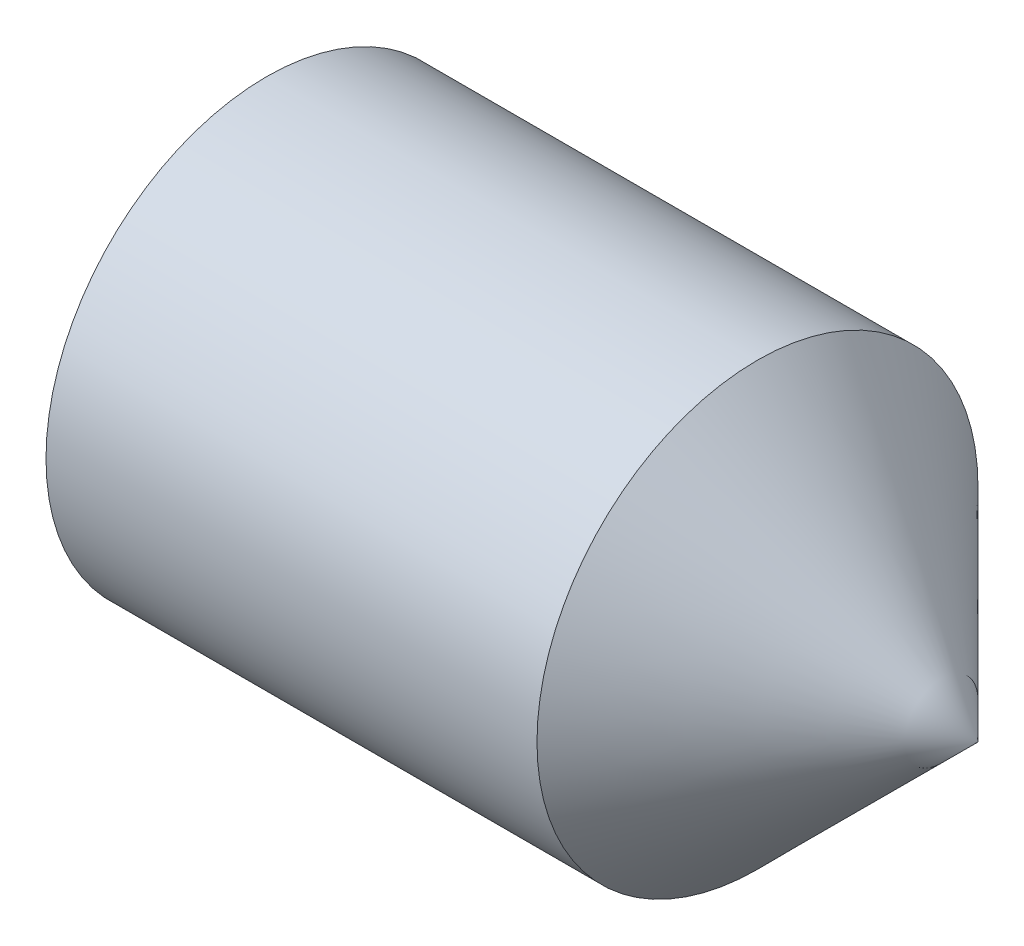
SolidWorks part; units mm, degrees
revolve "BaseBody" add sketch "BodySke" angle 360 about L5
sketch "BodySke" plane through (0, 0, 0) normal (0, 0, 1) x (1, 0, 0)
  line L0 (0, 0) -> (0, 2.4455)
  line L1 (0, 2.4455) -> (0.3201, 3)
  line L2 (0.3201, 3) -> (7, 3)
  line L3 (7, 3) -> (10, 0)
  line L4 (10, 0) -> (0, 0)
  line L5 (-12.7, 0) -> (88.9, 0) construction
  line L6 (7, -3) -> (10, 0) construction
  line L7 (0.5, 15.875) -> (0.5, -3.175) construction
  line L8 (0, -2.4455) -> (0.3201, -3) construction
  dimension "Diameter" = 6
  dimension "Drive_ch_ang" = 60
  dimension "Minor_dia" = 4.891
  dimension "Advance" = 1
  dimension "Cone_ang" = 90
  dimension "Length" = 10
cosmetic thread "ThreadCosmetic" [suppressed] parameters "Thread_minor"=4.891
ref_plane "Plane1" through (0, 0, 0) normal (0, 0, 1) x (1, 0, 0)
ref_plane "Plane2" through (0, 0, 0) normal (0, 1, 0) x (1, 0, 0)
ref_plane "Plane3" through (0, 0, 0) normal (1, 0, 0) x (0, 0, -1)
sketch "Sketch2" plane through (0, 0, 0) normal (-1, 0, 0) x (0, 0, 1)
  line L0 (0.866, 1.5) -> (-0.866, 1.5)
  line L1 (-0.866, 1.5) -> (-1.7321, 0)
  line L2 (0.866, 1.5) -> (1.7321, 0)
  line L3 (0.866, -1.5) -> (1.7321, 0)
  line L4 (0.866, -1.5) -> (-0.866, -1.5)
  line L5 (-0.866, -1.5) -> (-1.7321, 0)
  dimension "Hex_size" = 3
  dimension "D2" = 1.5
  dimension "D3" = 1.5
extrude "Hex" cut sketch "Sketch2" against normal blind 3.5
sketch "ThdSchSke" plane through (0, 0, 0) normal (0, 0, 1) x (1, 0, 0)
  line L0 (0.3201, -2.4455) -> (-0.0681, -3)
  line L1 (0.3201, -2.4455) -> (0.7084, -3)
  line L2 (0.7084, -3) -> (0.7084, -3.75)
  line L3 (-3.175, 0) -> (5.1513, 0) construction
  line L4 (0.3201, 3) -> (0.3201, -3) construction
  line L5 (0.7084, -3.75) -> (-0.0681, -3.75)
  line L6 (-0.0681, -3.75) -> (-0.0681, -3)
  dimension "Thread_minor" = 4.891
  dimension "Diameter" = 6
revolve "ThreadSchematic" [suppressed] cut sketch "ThdSchSke" angle 360 about L3
pattern_linear "ThdSchPat" [suppressed]
sketch "Croquis1" plane through (0, 0, 0) normal (0, 0, 1) x (1, 0, 0)
  line L0 (-5.1269, 0) -> (12.9192, 0) construction
equation "\"D2@Sketch2\" = \"Hex_size@Sketch2\" / 2"
equation "\"D3@Sketch2\" = \"Hex_size@Sketch2\" / 2"
equation "\"Thread_minor@ThreadCosmetic\" = \"Minor_dia@BodySke\""
equation "\"Thread_minor@ThdSchSke\" = \"Thread_minor@ThreadCosmetic\""
equation "\"Diameter@ThdSchSke\" = \"Diameter@BodySke\""
equation "\"Overcut@ThdSchSke\" = \"Diameter@BodySke\" * 1.25"
equation "\"Num_threads@ThdSchPat\" = int( (\"Length@BodySke\" - ( ( ( \"Diameter@BodySke\" - \"Minor_dia@BodySke\" ) * 0.5 ) / tan( \"Drive_ch_ang@BodySke\" * 0.017453292 ) ) - ( ( \"Diameter@BodySke\" * 0.5 ) / tan( \"Cone_ang@BodySke\" * 0.008726646 ) ) ) / \"Advance@BodySke\" + 0.999 )  + 1"
equation "\"Advance@ThdSchPat\" = (\"Length@BodySke\" - ( ( ( \"Diameter@BodySke\" - \"Minor_dia@BodySke\" ) * 0.5 ) / tan( \"Drive_ch_ang@BodySke\" * 0.017453292 ) ) - ( ( \"Diameter@BodySke\" * 0.5 ) / tan( \"Cone_ang@BodySke\" * 0.008726646 ) ) ) /  (\"Num_threads@ThdSchPat\" - 1) 'relax it"
equation "' \"Num_threads@ThdSchPat\" = \"Num_threads@ThdSchPat\" - sgn( \"Num_threads@ThdSchPat\" - 1) '---chamfered tips only---"
